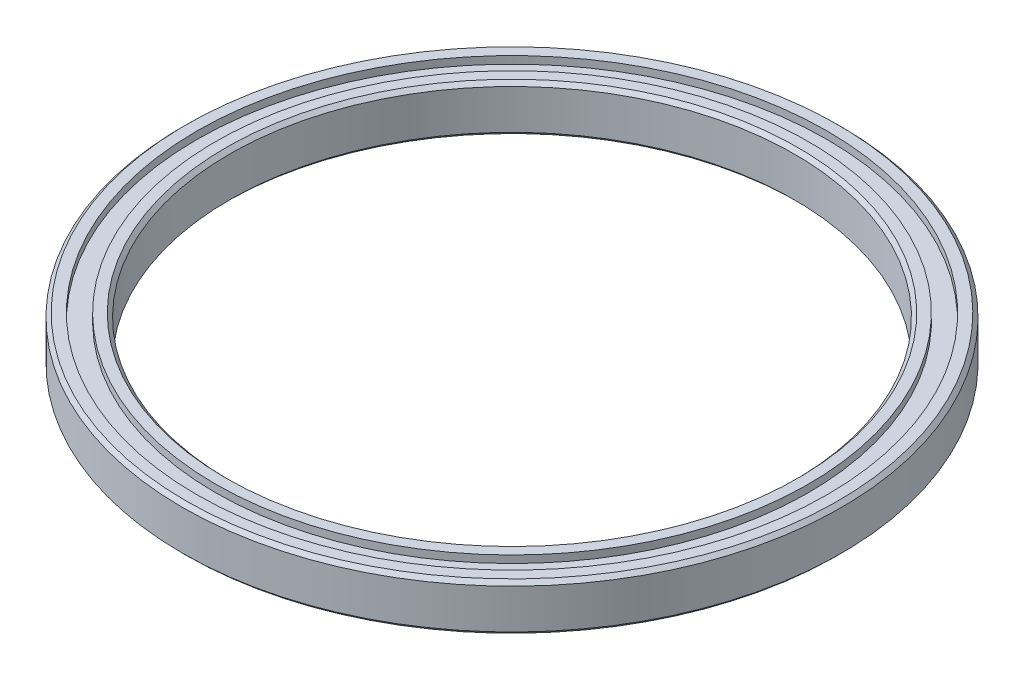
SolidWorks part; units mm, degrees
material "AISI 347 退火不锈钢 (SS)"
ref_plane "前视基准面" through (0, 0, 0) normal (0, 0, 1) x (1, 0, 0)
ref_plane "上视基准面" through (0, 0, 0) normal (0, 1, 0) x (1, 0, 0)
ref_plane "右视基准面" through (0, 0, 0) normal (1, 0, 0) x (0, 0, -1)
sketch "草图1" plane through (0, 0, 0) normal (0, 1, 0) x (1, 0, 0)
  circle A0 centre (0, 0) radius 38.1
  circle A1 centre (0, 0) radius 44.45
  dimension "D1" = 88.9
  dimension "D2" = 76.2
extrude "凸台-拉伸1" add sketch "草图1" along normal blind 6.35
sketch "草图2" plane through (0, 6.35, 0) normal (0, 1, 0) x (1, 0, 0)
  circle A0 centre (0, 0) radius 40
  circle A1 centre (0, 0) radius 42.5
  dimension "D1" = 80
  dimension "D2" = 85
extrude "切除-拉伸1" cut sketch "草图2" against normal blind 1
sketch "草图3" plane through (0, 0, 0) normal (0, -1, 0) x (1, 0, 0)
  circle A0 centre (0, 0) radius 40
  circle A1 centre (0, 0) radius 42.5
  dimension "D1" = 80
  dimension "D2" = 85
extrude "切除-拉伸2" cut sketch "草图3" against normal blind 1
chamfer "倒角1" distance 0.5 angle 45 4 edges at (0, 6.35, 44.45) (0, 0, 44.45) (0, 0, 38.1) (0, 6.35, 38.1)
